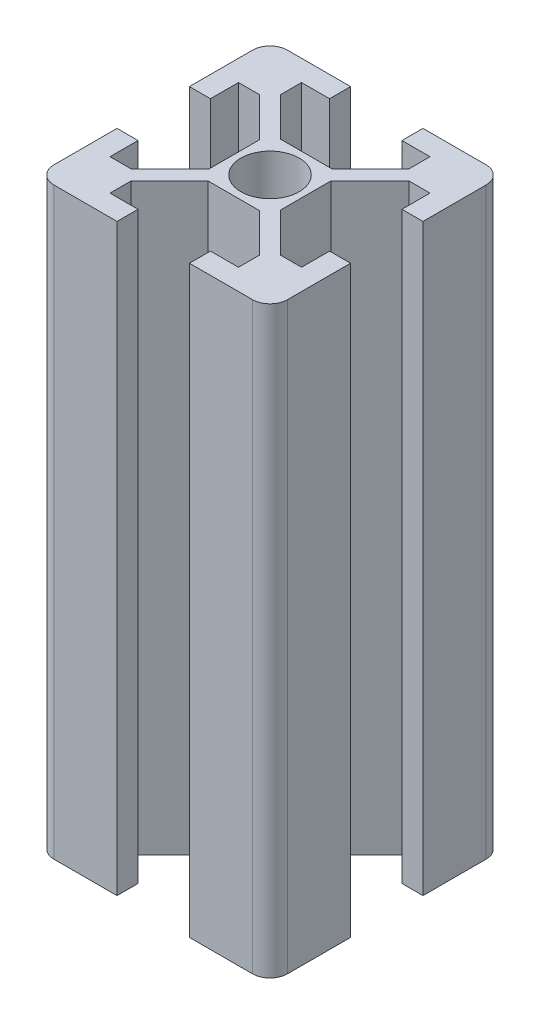
SolidWorks part; units mm, degrees
ref_plane "前视基准面" through (0, 0, 0) normal (0, 0, 1) x (1, 0, 0)
ref_plane "上视基准面" through (0, 0, 0) normal (0, 1, 0) x (1, 0, 0)
ref_plane "右视基准面" through (0, 0, 0) normal (1, 0, 0) x (0, 0, -1)
sketch "草图1" plane through (0, 0, 0) normal (0, 1, 0) x (1, 0, 0)
  line L0 (-48.2474, 7.8059) -> (-46.4474, 7.8059)
  line L1 (-46.7474, 20.9059) -> (-29.7474, 20.9059)
  line L2 (-48.2474, 19.4059) -> (-48.2474, 2.4059)
  line L3 (-46.7474, 0.9059) -> (-29.7474, 0.9059)
  line L4 (-28.2474, 19.4059) -> (-28.2474, 2.4059)
  line L5 (-48.2474, 20.9059) -> (-28.2474, 0.9059) construction
  line L6 (-48.2474, 0.9059) -> (-28.2474, 20.9059) construction
  line L7 (-41.3015, 14.0059) -> (-35.1933, 14.0059)
  line L8 (-41.3015, 14.0059) -> (-41.3015, 7.8059)
  line L9 (-41.3015, 7.8059) -> (-35.1933, 7.8059)
  line L10 (-35.1933, 14.0059) -> (-35.1933, 7.8059)
  line L11 (-41.3015, 14.0059) -> (-35.1933, 7.8059) construction
  line L12 (-41.3015, 7.8059) -> (-35.1933, 14.0059) construction
  line L13 (-46.4474, 7.8059) -> (-46.4474, 5.4059)
  line L14 (-46.4474, 5.4059) -> (-44.6445, 5.4059)
  line L15 (-44.6445, 5.4059) -> (-41.3015, 8.7488)
  line L16 (-43.7474, 17.3029) -> (-40.4045, 13.96)
  line L17 (-43.7474, 19.1059) -> (-43.7474, 17.3029)
  line L18 (-41.3474, 19.1059) -> (-43.7474, 19.1059)
  line L19 (-41.3474, 20.9059) -> (-41.3474, 19.1059)
  line L20 (-31.8504, 16.4059) -> (-35.1933, 13.063)
  line L21 (-30.0474, 16.4059) -> (-31.8504, 16.4059)
  line L22 (-30.0474, 14.0059) -> (-30.0474, 16.4059)
  line L23 (-28.2474, 14.0059) -> (-30.0474, 14.0059)
  line L24 (-32.7474, 4.5088) -> (-36.0903, 7.8518)
  line L25 (-32.7474, 2.7059) -> (-32.7474, 4.5088)
  line L26 (-35.1474, 2.7059) -> (-32.7474, 2.7059)
  line L27 (-35.1474, 0.9059) -> (-35.1474, 2.7059)
  line L28 (-41.3474, 0.9059) -> (-41.3474, 2.7059)
  line L29 (-41.3474, 2.7059) -> (-43.7474, 2.7059)
  line L30 (-43.7474, 2.7059) -> (-43.7474, 4.5088)
  line L31 (-43.7474, 4.5088) -> (-40.4045, 7.8518)
  line L32 (-46.4474, 16.4059) -> (-44.6445, 16.4059)
  line L33 (-44.6445, 16.4059) -> (-41.3015, 13.063)
  line L34 (-46.4474, 14.0059) -> (-46.4474, 16.4059)
  line L35 (-48.2474, 14.0059) -> (-46.4474, 14.0059)
  line L36 (-32.7474, 19.1059) -> (-32.7474, 17.3029)
  line L37 (-32.7474, 17.3029) -> (-36.0903, 13.96)
  line L38 (-35.1474, 19.1059) -> (-32.7474, 19.1059)
  line L39 (-35.1474, 20.9059) -> (-35.1474, 19.1059)
  line L40 (-30.0474, 5.4059) -> (-31.8504, 5.4059)
  line L41 (-31.8504, 5.4059) -> (-35.1933, 8.7488)
  line L42 (-30.0474, 7.8059) -> (-30.0474, 5.4059)
  line L43 (-28.2474, 7.8059) -> (-30.0474, 7.8059)
  circle A0 centre (-38.2474, 10.9059) radius 2.5
  arc A1 (-48.2474, 19.4059) -> (-46.7474, 20.9059) centre (-46.7474, 19.4059) cw
  arc A2 (-48.2474, 2.4059) -> (-46.7474, 0.9059) centre (-46.7474, 2.4059) ccw
  arc A3 (-29.7474, 20.9059) -> (-28.2474, 19.4059) centre (-29.7474, 19.4059) cw
  arc A4 (-28.2474, 2.4059) -> (-29.7474, 0.9059) centre (-29.7474, 2.4059) cw
  point P0 (-38.2474, 10.9059)
  point P19 (-38.2474, 10.9059)
  point P25 (-38.2474, 10.9059)
  point P31 (-38.2474, 10.9059)
  point P37 (-38.2474, 10.9059)
  point P59 (-38.2474, 10.9059)
extrude "凸台-拉伸1" add sketch "草图1" along normal blind 50
